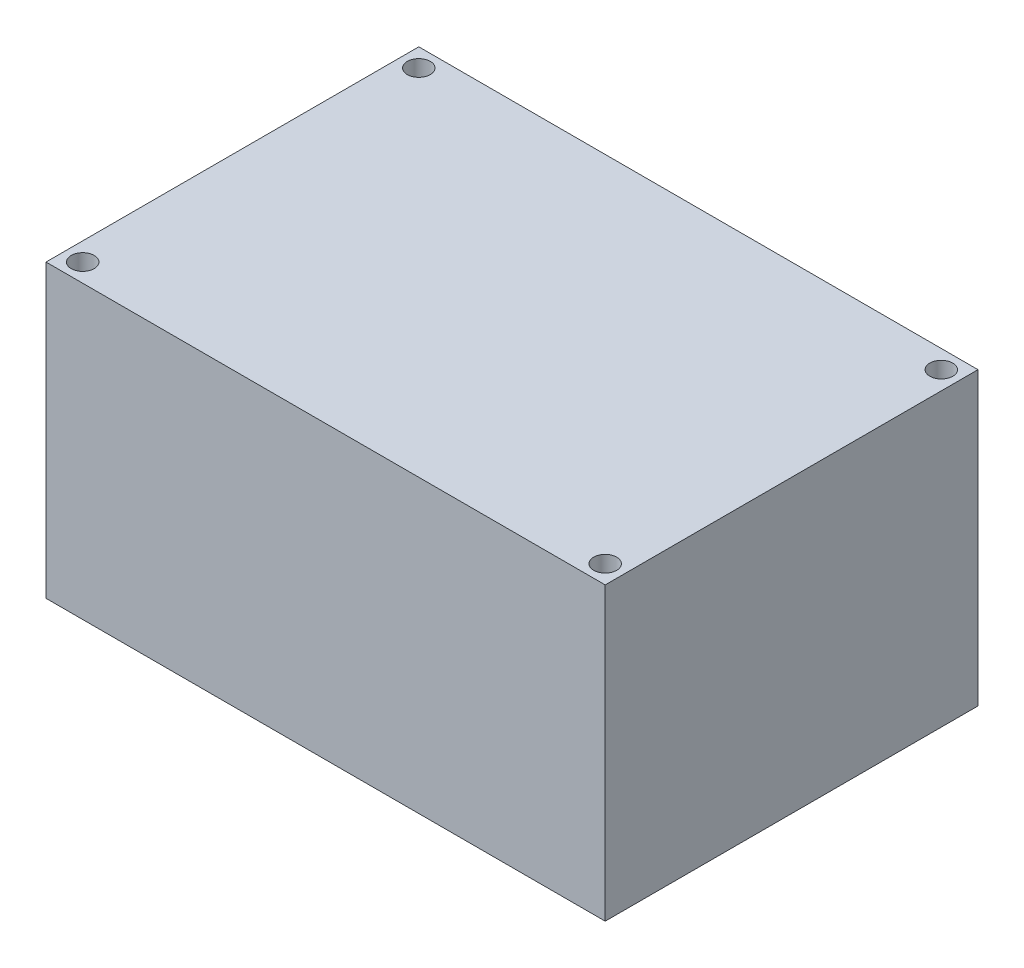
SolidWorks part; units mm, degrees
ref_plane "Front Plane" through (0, 0, 0) normal (0, 0, 1) x (1, 0, 0)
ref_plane "Top Plane" through (0, 0, 0) normal (0, 1, 0) x (1, 0, 0)
ref_plane "Right Plane" through (0, 0, 0) normal (1, 0, 0) x (0, 0, -1)
sketch "Sketch1" plane through (0, 0, 0) normal (0, 1, 0) x (1, 0, 0)
  line L1 (0, 0) -> (-60.96, 0)
  line L2 (0, 0) -> (0, 40.64)
  line L3 (0, 40.64) -> (-60.96, 40.64)
  line L4 (-60.96, 0) -> (-60.96, 40.64)
  dimension "D1" = 60.96
  dimension "D2" = 40.64
extrude "Boss-Extrude1" add sketch "Sketch1" along normal blind 31.75 contours L3 L4 L1 L2
sketch "Sketch2" plane through (0, 31.75, 0) normal (0, 1, 0) x (1, 0, 0)
  text T0 "Power Distribution" font "Century Gothic" height in points 16
sketch "Sketch3" plane through (0, 31.75, 0) normal (0, 1, 0) x (1, 0, 0)
  line L0 (-60.96, 0) -> (-60.96, 2)
  line L1 (-60.96, 0) -> (-60.96, 40.64) construction
  line L2 (-60.96, 40.64) -> (-60.96, 38.64)
  line L3 (0, 0) -> (0, 2)
  line L4 (0, 0) -> (0, 40.64) construction
  line L5 (0, 40.64) -> (0, 38.64)
  line L6 (0, 0) -> (-1.9997, 0)
  line L7 (0, 0) -> (-60.96, 0) construction
  line L8 (0, 40.64) -> (-1.9997, 40.64)
  line L9 (0, 40.64) -> (-60.96, 40.64) construction
  line L10 (-60.96, 0) -> (-58.96, 0)
  line L11 (-60.96, 40.64) -> (-58.96, 40.64)
  line L12 (-60.96, 2) -> (0, 2)
  line L13 (-58.96, 0) -> (-58.96, 40.64)
  line L14 (-60.96, 38.64) -> (0, 38.64)
  line L15 (-1.9997, 40.64) -> (-1.9997, 0)
  circle A0 centre (-58.96, 2) radius 1.252
  circle A1 centre (-58.96, 38.64) radius 1.2525
  circle A2 centre (-1.9997, 38.64) radius 1.25
  circle A3 centre (-1.9997, 2) radius 1.2492
  dimension "D4" = 2.5
  dimension "D1" = 2
  dimension "D2" = 2
  dimension "D3" = 2
extrude "Cut-Extrude1" cut sketch "Sketch3" against normal through all contours L12 A3 L15 | L15 A3 L12 | L12 A3 L15 | L15 A3 L12 | L15 A2 L14 | L14 A2 L15 | L15 A2 L14 | L14 A2 L15 | L14 A1 L13 | L13 A1 L14 | L14 A1 L13 | L13 A1 L14 | L13 A0 L12 | L12 A0 L13 | L13 A0 L12 | L12 A0 L13
